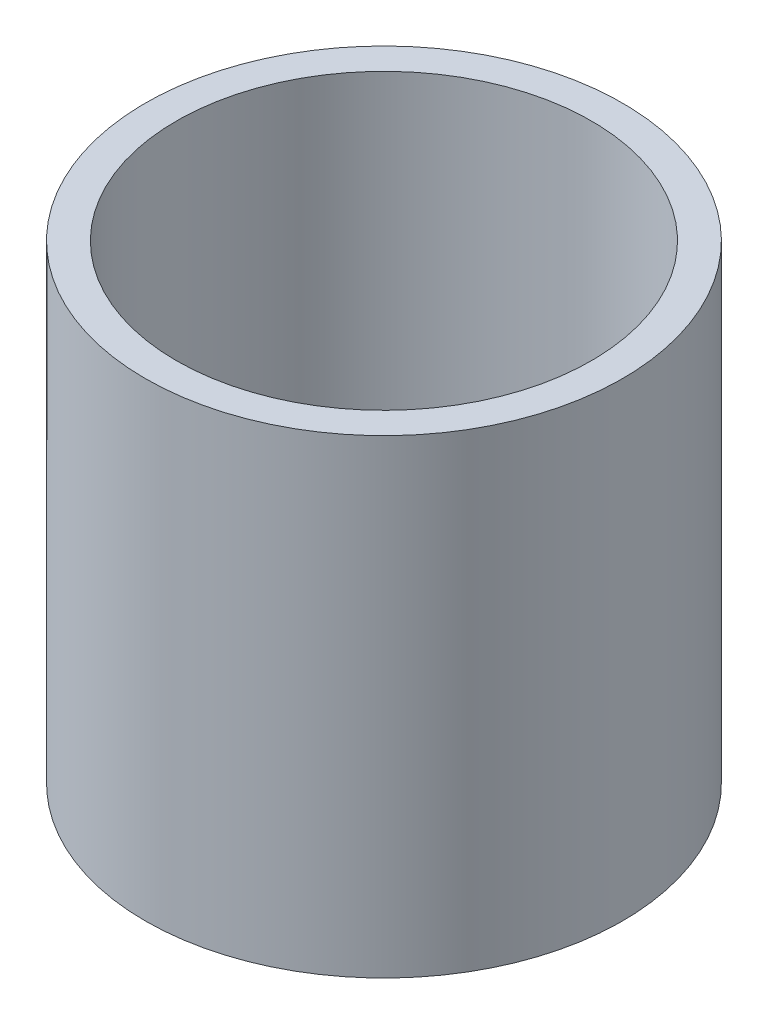
SolidWorks part; units mm, degrees
ref_plane "Front Plane" through (0, 0, 0) normal (0, 0, 1) x (1, 0, 0)
ref_plane "Top Plane" through (0, 0, 0) normal (0, 1, 0) x (1, 0, 0)
ref_plane "Right Plane" through (0, 0, 0) normal (1, 0, 0) x (0, 0, -1)
sketch "Sketch1" plane through (0, 0, 0) normal (0, 1, 0) x (1, 0, 0)
  circle A0 centre (0, 0) radius 12.7
  circle A1 centre (0, 0) radius 11.049
  dimension "D1" = 25.4
  dimension "D2" = 1.651
extrude "Boss-Extrude1" add sketch "Sketch1" along normal blind 25
